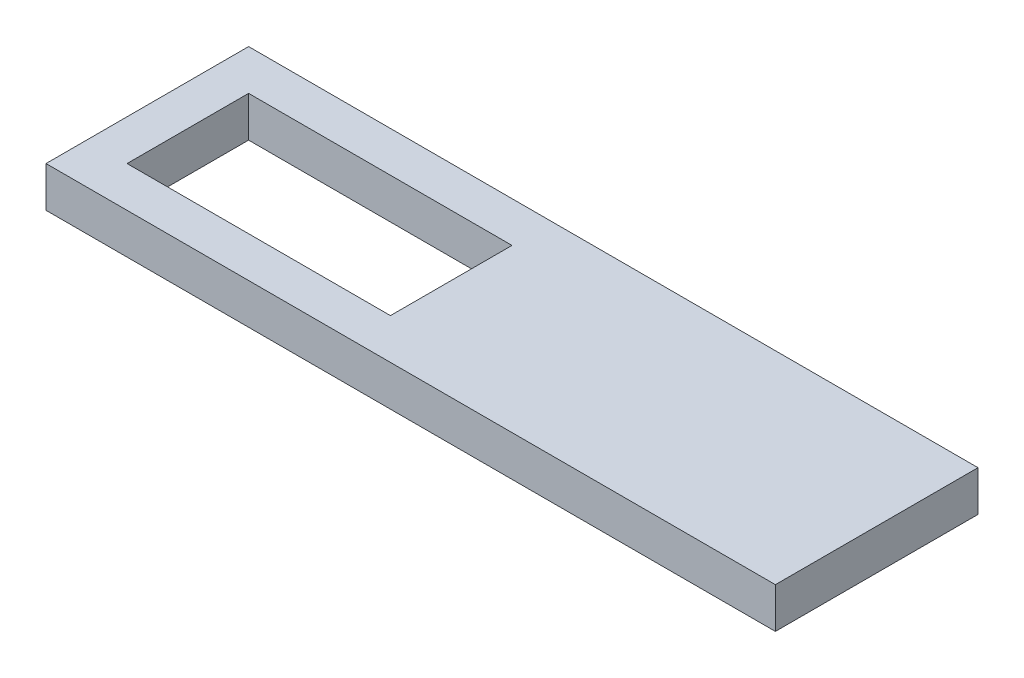
SolidWorks part; units mm, degrees
ref_plane "Front Plane" through (0, 0, 0) normal (0, 0, 1) x (1, 0, 0)
ref_plane "Top Plane" through (0, 0, 0) normal (0, 1, 0) x (1, 0, 0)
ref_plane "Right Plane" through (0, 0, 0) normal (1, 0, 0) x (0, 0, -1)
sketch "Sketch1" plane through (0, 0, 0) normal (0, 0, 1) x (1, 0, 0)
  line L0 (38.1, -304.8) -> (38.1, 0) construction
  line L1 (38.1, -152.4) -> (-76.2, -152.4)
  line L2 (38.1, -152.4) -> (38.1, -158.75)
  line L3 (38.1, -158.75) -> (-76.2, -158.75)
  line L4 (-76.2, -152.4) -> (-76.2, -158.75)
  line L6 (-38.1, -304.8) -> (-38.1, 0) construction
  dimension "D1" = 6.35
  dimension "D2" = 38.1
extrude "Boss-Extrude1" add sketch "Sketch1" along normal blind 31.75
sketch "Sketch2" plane through (0, -158.75, 0) normal (0, -1, 0) x (1, 0, 0)
  line L1 (-28.575, 6.35) -> (-69.85, 6.35)
  line L2 (-28.575, 6.35) -> (-28.575, 25.4)
  line L3 (-28.575, 25.4) -> (-69.85, 25.4)
  line L4 (-69.85, 6.35) -> (-69.85, 25.4)
  line L6 (-76.2, 15.875) -> (38.1, 15.875) construction
  line L7 (-76.2, 31.75) -> (-76.2, 0) construction
  line L8 (38.1, 31.75) -> (38.1, 0) construction
  dimension "D1" = 6.35
  dimension "D2" = 41.275
  dimension "D3" = 19.05
extrude "Cut-Extrude2" cut sketch "Sketch2" against normal through all
